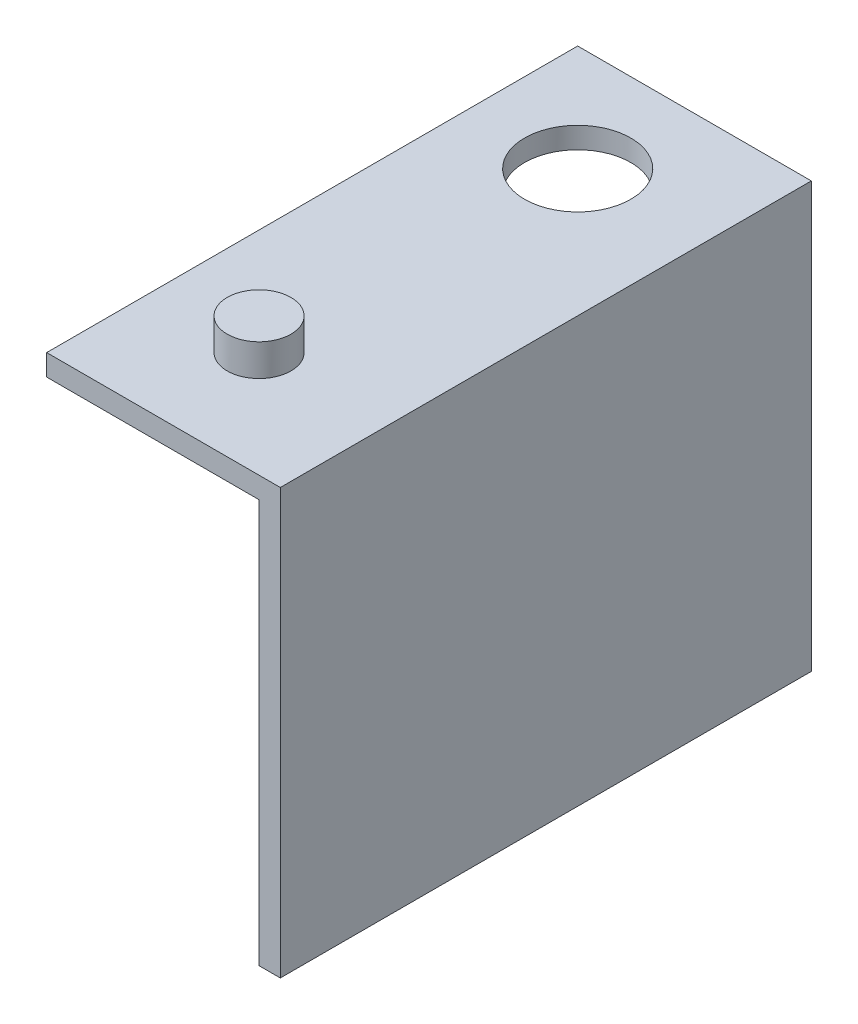
SolidWorks part; units mm, degrees
ref_plane "Alzado" through (0, 0, 0) normal (0, 0, 1) x (1, 0, 0)
ref_plane "Planta" through (0, 0, 0) normal (0, 1, 0) x (1, 0, 0)
ref_plane "Vista lateral" through (0, 0, 0) normal (1, 0, 0) x (0, 0, -1)
sketch "Croquis1" plane through (0, 0, 0) normal (0, 0, 1) x (1, 0, 0)
  line L2 (0, 0) -> (0, 2)
  line L3 (0, 2) -> (22, 2)
  line L9 (22, 2) -> (22, -38)
  line L10 (22, -38) -> (20, -38)
  line L11 (20, -38) -> (20, 0)
  line L12 (20, 0) -> (0, 0)
  dimension "D1" = 2
  dimension "D2" = 2
  dimension "D3" = 40
  dimension "D4" = 22
extrude "Saliente-Extruir1" add sketch "Croquis1" along normal blind 50
sketch "Croquis2" plane through (0, 2, 0) normal (0, 1, 0) x (1, 0, 0)
  line L0 (0, -10) -> (10, -10) construction
  line L2 (0, -50) -> (0, 0) construction
  line L4 (10, -10) -> (10, 0) construction
  line L5 (22, 0) -> (0, 0) construction
  circle A0 centre (10, -10) radius 5
  dimension "D1" = 10
  dimension "D2" = 10
extrude "Cortar-Extruir1" cut sketch "Croquis2" against normal up to next
sketch "Croquis3" plane through (0, 2, 0) normal (0, 1, 0) x (1, 0, 0)
  line L0 (0, -40) -> (10, -40) construction
  line L1 (0, -50) -> (0, 0) construction
  line L2 (10, -40) -> (10, -50) construction
  line L3 (22, -50) -> (0, -50) construction
  circle A0 centre (10, -40) radius 3
  dimension "D3" = 6
  dimension "D1" = 10
  dimension "D2" = 10
extrude "Saliente-Extruir2" add sketch "Croquis3" along normal blind 3
